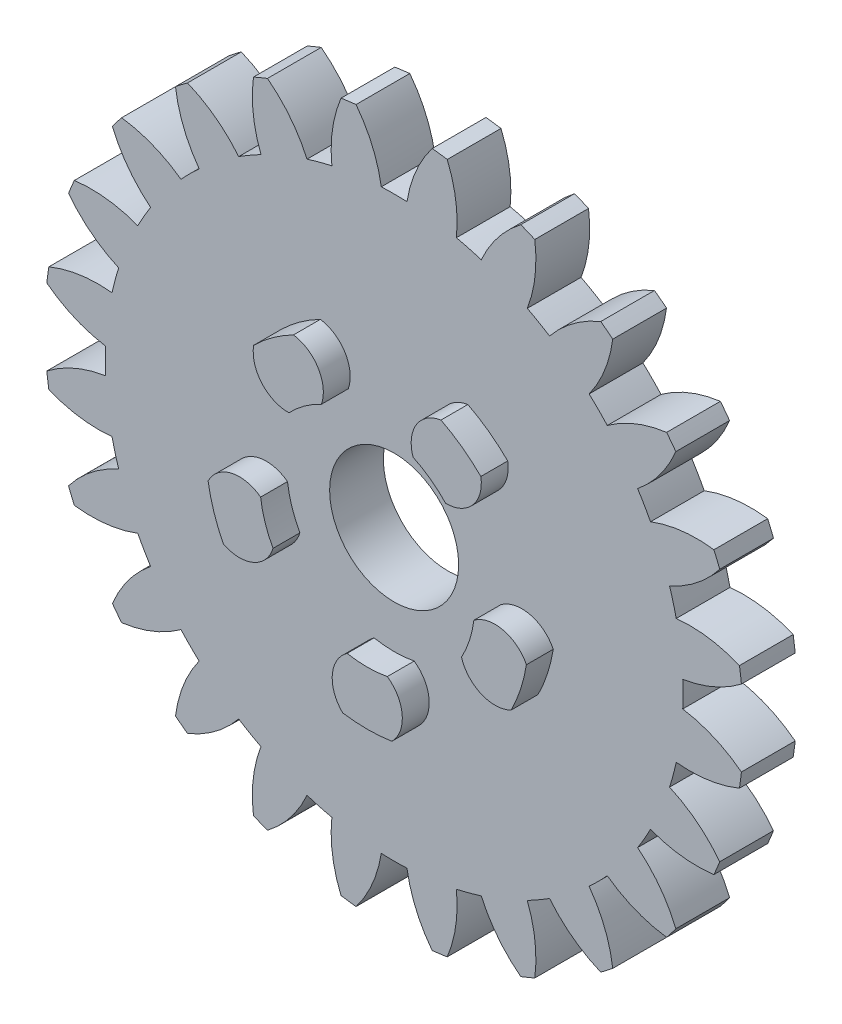
SolidWorks part; units mm, degrees
ref_plane "Front Plane" through (0, 0, 0) normal (0, 0, 1) x (1, 0, 0)
ref_plane "Top Plane" through (0, 0, 0) normal (0, 1, 0) x (1, 0, 0)
ref_plane "Right Plane" through (0, 0, 0) normal (1, 0, 0) x (0, 0, -1)
sketch "Sketch1" plane through (0, 0, 0) normal (0, 0, 1) x (1, 0, 0)
  circle A0 centre (0, 0) radius 3
  arc A96 (-32.3065, 3.5416) -> (-26.8474, 1.1963) centre (-24.9877, 13.0513) ccw
  arc A97 (-26.8474, 1.1963) -> (-26.8474, -1.1963) centre (0, 0) ccw
  arc A98 (-26.8474, -1.1963) -> (-32.3065, -3.5416) centre (-24.9877, -13.0513) ccw
  arc A99 (-32.3065, -3.5416) -> (-32.1223, -4.9406) centre (0, 0) ccw
  arc A100 (-32.1223, -4.9406) -> (-26.2422, -5.7931) centre (-27.5142, 6.1393) ccw
  arc A101 (-26.2422, -5.7931) -> (-25.6229, -8.1041) centre (0, 0) ccw
  arc A102 (-25.6229, -8.1041) -> (-30.289, -11.7824) centre (-20.7583, -19.0739) ccw
  arc A103 (-30.289, -11.7824) -> (-29.749, -13.0861) centre (0, 0) ccw
  arc A104 (-29.749, -13.0861) -> (-23.8486, -12.3877) centre (-28.1656, -1.191) ccw
  arc A105 (-23.8486, -12.3877) -> (-22.6523, -14.4597) centre (0, 0) ccw
  arc A106 (-22.6523, -14.4597) -> (-26.2074, -19.2203) centre (-15.1143, -23.7966) ccw
  arc A107 (-26.2074, -19.2203) -> (-25.3484, -20.3398) centre (0, 0) ccw
  arc A108 (-25.3484, -20.3398) -> (-19.8299, -18.138) centre (-26.8976, -8.4403) ccw
  arc A109 (-19.8299, -18.138) -> (-18.138, -19.8299) centre (0, 0) ccw
  arc A110 (-18.138, -19.8299) -> (-20.3398, -25.3484) centre (-8.4403, -26.8976) ccw
  arc A111 (-20.3398, -25.3484) -> (-19.2203, -26.2074) centre (0, 0) ccw
  arc A112 (-19.2203, -26.2074) -> (-14.4597, -22.6523) centre (-23.7966, -15.1143) ccw
  arc A113 (-14.4597, -22.6523) -> (-12.3877, -23.8486) centre (0, 0) ccw
  arc A114 (-12.3877, -23.8486) -> (-13.0861, -29.749) centre (-1.191, -28.1656) ccw
  arc A115 (-13.0861, -29.749) -> (-11.7824, -30.289) centre (0, 0) ccw
  arc A116 (-11.7824, -30.289) -> (-8.1041, -25.6229) centre (-19.0739, -20.7583) ccw
  arc A117 (-8.1041, -25.6229) -> (-5.7931, -26.2422) centre (0, 0) ccw
  arc A118 (-5.7931, -26.2422) -> (-4.9406, -32.1223) centre (6.1393, -27.5142) ccw
  arc A119 (-4.9406, -32.1223) -> (-3.5416, -32.3065) centre (0, 0) ccw
  arc A120 (-3.5416, -32.3065) -> (-1.1963, -26.8474) centre (-13.0513, -24.9877) ccw
  arc A121 (-1.1963, -26.8474) -> (1.1963, -26.8474) centre (0, 0) ccw
  arc A122 (1.1963, -26.8474) -> (3.5416, -32.3065) centre (13.0513, -24.9877) ccw
  arc A123 (3.5416, -32.3065) -> (4.9406, -32.1223) centre (0, 0) ccw
  arc A124 (4.9406, -32.1223) -> (5.7931, -26.2422) centre (-6.1393, -27.5142) ccw
  arc A125 (5.7931, -26.2422) -> (8.1041, -25.6229) centre (0, 0) ccw
  arc A126 (8.1041, -25.6229) -> (11.7824, -30.289) centre (19.0739, -20.7583) ccw
  arc A127 (11.7824, -30.289) -> (13.0861, -29.749) centre (0, 0) ccw
  arc A128 (13.0861, -29.749) -> (12.3877, -23.8486) centre (1.191, -28.1656) ccw
  arc A129 (12.3877, -23.8486) -> (14.4597, -22.6523) centre (0, 0) ccw
  arc A130 (14.4597, -22.6523) -> (19.2203, -26.2074) centre (23.7966, -15.1143) ccw
  arc A131 (19.2203, -26.2074) -> (20.3398, -25.3484) centre (0, 0) ccw
  arc A132 (20.3398, -25.3484) -> (18.138, -19.8299) centre (8.4403, -26.8976) ccw
  arc A133 (18.138, -19.8299) -> (19.8299, -18.138) centre (0, 0) ccw
  arc A134 (19.8299, -18.138) -> (25.3484, -20.3398) centre (26.8976, -8.4403) ccw
  arc A135 (25.3484, -20.3398) -> (26.2074, -19.2203) centre (0, 0) ccw
  arc A136 (26.2074, -19.2203) -> (22.6523, -14.4597) centre (15.1143, -23.7966) ccw
  arc A137 (22.6523, -14.4597) -> (23.8486, -12.3877) centre (0, 0) ccw
  arc A138 (23.8486, -12.3877) -> (29.749, -13.0861) centre (28.1656, -1.191) ccw
  arc A139 (29.749, -13.0861) -> (30.289, -11.7824) centre (0, 0) ccw
  arc A140 (30.289, -11.7824) -> (25.6229, -8.1041) centre (20.7583, -19.0739) ccw
  arc A141 (25.6229, -8.1041) -> (26.2422, -5.7931) centre (0, 0) ccw
  arc A142 (26.2422, -5.7931) -> (32.1223, -4.9406) centre (27.5142, 6.1393) ccw
  arc A143 (32.1223, -4.9406) -> (32.3065, -3.5416) centre (0, 0) ccw
  arc A144 (32.3065, -3.5416) -> (26.8474, -1.1963) centre (24.9877, -13.0513) ccw
  arc A145 (26.8474, -1.1963) -> (26.8474, 1.1963) centre (0, 0) ccw
  arc A146 (26.8474, 1.1963) -> (32.3065, 3.5416) centre (24.9877, 13.0513) ccw
  arc A147 (32.3065, 3.5416) -> (32.1223, 4.9406) centre (0, 0) ccw
  arc A148 (32.1223, 4.9406) -> (26.2422, 5.7931) centre (27.5142, -6.1393) ccw
  arc A149 (26.2422, 5.7931) -> (25.6229, 8.1041) centre (0, 0) ccw
  arc A150 (25.6229, 8.1041) -> (30.289, 11.7824) centre (20.7583, 19.0739) ccw
  arc A151 (30.289, 11.7824) -> (29.749, 13.0861) centre (0, 0) ccw
  arc A152 (29.749, 13.0861) -> (23.8486, 12.3877) centre (28.1656, 1.191) ccw
  arc A153 (23.8486, 12.3877) -> (22.6523, 14.4597) centre (0, 0) ccw
  arc A154 (22.6523, 14.4597) -> (26.2074, 19.2203) centre (15.1143, 23.7966) ccw
  arc A155 (26.2074, 19.2203) -> (25.3484, 20.3398) centre (0, 0) ccw
  arc A156 (25.3484, 20.3398) -> (19.8299, 18.138) centre (26.8976, 8.4403) ccw
  arc A157 (19.8299, 18.138) -> (18.138, 19.8299) centre (0, 0) ccw
  arc A158 (18.138, 19.8299) -> (20.3398, 25.3484) centre (8.4403, 26.8976) ccw
  arc A159 (20.3398, 25.3484) -> (19.2203, 26.2074) centre (0, 0) ccw
  arc A160 (19.2203, 26.2074) -> (14.4597, 22.6523) centre (23.7966, 15.1143) ccw
  arc A161 (14.4597, 22.6523) -> (12.3877, 23.8486) centre (0, 0) ccw
  arc A162 (12.3877, 23.8486) -> (13.0861, 29.749) centre (1.191, 28.1656) ccw
  arc A163 (13.0861, 29.749) -> (11.7824, 30.289) centre (0, 0) ccw
  arc A164 (11.7824, 30.289) -> (8.1041, 25.6229) centre (19.0739, 20.7583) ccw
  arc A165 (8.1041, 25.6229) -> (5.7931, 26.2422) centre (0, 0) ccw
  arc A166 (5.7931, 26.2422) -> (4.9406, 32.1223) centre (-6.1393, 27.5142) ccw
  arc A167 (4.9406, 32.1223) -> (3.5416, 32.3065) centre (0, 0) ccw
  arc A168 (3.5416, 32.3065) -> (1.1963, 26.8474) centre (13.0513, 24.9877) ccw
  arc A169 (1.1963, 26.8474) -> (-1.1963, 26.8474) centre (0, 0) ccw
  arc A170 (-1.1963, 26.8474) -> (-3.5416, 32.3065) centre (-13.0513, 24.9877) ccw
  arc A171 (-3.5416, 32.3065) -> (-4.9406, 32.1223) centre (0, 0) ccw
  arc A172 (-4.9406, 32.1223) -> (-5.7931, 26.2422) centre (6.1393, 27.5142) ccw
  arc A173 (-5.7931, 26.2422) -> (-8.1041, 25.6229) centre (0, 0) ccw
  arc A174 (-8.1041, 25.6229) -> (-11.7824, 30.289) centre (-19.0739, 20.7583) ccw
  arc A175 (-11.7824, 30.289) -> (-13.0861, 29.749) centre (0, 0) ccw
  arc A176 (-13.0861, 29.749) -> (-12.3877, 23.8486) centre (-1.191, 28.1656) ccw
  arc A177 (-12.3877, 23.8486) -> (-14.4597, 22.6523) centre (0, 0) ccw
  arc A178 (-14.4597, 22.6523) -> (-19.2203, 26.2074) centre (-23.7966, 15.1143) ccw
  arc A179 (-19.2203, 26.2074) -> (-20.3398, 25.3484) centre (0, 0) ccw
  arc A180 (-20.3398, 25.3484) -> (-18.138, 19.8299) centre (-8.4403, 26.8976) ccw
  arc A181 (-18.138, 19.8299) -> (-19.8299, 18.138) centre (0, 0) ccw
  arc A182 (-19.8299, 18.138) -> (-25.3484, 20.3398) centre (-26.8976, 8.4403) ccw
  arc A183 (-25.3484, 20.3398) -> (-26.2074, 19.2203) centre (0, 0) ccw
  arc A184 (-26.2074, 19.2203) -> (-22.6523, 14.4597) centre (-15.1143, 23.7966) ccw
  arc A185 (-22.6523, 14.4597) -> (-23.8486, 12.3877) centre (0, 0) ccw
  arc A186 (-23.8486, 12.3877) -> (-29.749, 13.0861) centre (-28.1656, 1.191) ccw
  arc A187 (-29.749, 13.0861) -> (-30.289, 11.7824) centre (0, 0) ccw
  arc A188 (-30.289, 11.7824) -> (-25.6229, 8.1041) centre (-20.7583, 19.0739) ccw
  arc A189 (-25.6229, 8.1041) -> (-26.2422, 5.7931) centre (0, 0) ccw
  arc A190 (-26.2422, 5.7931) -> (-32.1223, 4.9406) centre (-27.5142, -6.1393) ccw
  arc A191 (-32.1223, 4.9406) -> (-32.3065, 3.5416) centre (0, 0) ccw
  arc A192 (-32.3065, 3.5416) -> (-26.8474, 1.1963) centre (-24.9877, 13.0513) ccw
  arc A193 (-26.8474, 1.1963) -> (-26.8474, -1.1963) centre (0, 0) ccw
  arc A194 (-26.8474, -1.1963) -> (-32.3065, -3.5416) centre (-24.9877, -13.0513) ccw
  arc A195 (-32.3065, -3.5416) -> (-32.1223, -4.9406) centre (0, 0) ccw
  arc A196 (-32.1223, -4.9406) -> (-26.2422, -5.7931) centre (-27.5142, 6.1393) ccw
  arc A197 (-26.2422, -5.7931) -> (-25.6229, -8.1041) centre (0, 0) ccw
  arc A198 (-25.6229, -8.1041) -> (-30.289, -11.7824) centre (-20.7583, -19.0739) ccw
  arc A199 (-30.289, -11.7824) -> (-29.749, -13.0861) centre (0, 0) ccw
  arc A200 (-29.749, -13.0861) -> (-23.8486, -12.3877) centre (-28.1656, -1.191) ccw
  arc A201 (-23.8486, -12.3877) -> (-22.6523, -14.4597) centre (0, 0) ccw
  arc A202 (-22.6523, -14.4597) -> (-26.2074, -19.2203) centre (-15.1143, -23.7966) ccw
  arc A203 (-26.2074, -19.2203) -> (-25.3484, -20.3398) centre (0, 0) ccw
  arc A204 (-25.3484, -20.3398) -> (-19.8299, -18.138) centre (-26.8976, -8.4403) ccw
  arc A205 (-19.8299, -18.138) -> (-18.138, -19.8299) centre (0, 0) ccw
  arc A206 (-18.138, -19.8299) -> (-20.3398, -25.3484) centre (-8.4403, -26.8976) ccw
  arc A207 (-20.3398, -25.3484) -> (-19.2203, -26.2074) centre (0, 0) ccw
  arc A208 (-19.2203, -26.2074) -> (-14.4597, -22.6523) centre (-23.7966, -15.1143) ccw
  arc A209 (-14.4597, -22.6523) -> (-12.3877, -23.8486) centre (0, 0) ccw
  arc A210 (-12.3877, -23.8486) -> (-13.0861, -29.749) centre (-1.191, -28.1656) ccw
  arc A211 (-13.0861, -29.749) -> (-11.7824, -30.289) centre (0, 0) ccw
  arc A212 (-11.7824, -30.289) -> (-8.1041, -25.6229) centre (-19.0739, -20.7583) ccw
  arc A213 (-8.1041, -25.6229) -> (-5.7931, -26.2422) centre (0, 0) ccw
  arc A214 (-5.7931, -26.2422) -> (-4.9406, -32.1223) centre (6.1393, -27.5142) ccw
  arc A215 (-4.9406, -32.1223) -> (-3.5416, -32.3065) centre (0, 0) ccw
  arc A216 (-3.5416, -32.3065) -> (-1.1963, -26.8474) centre (-13.0513, -24.9877) ccw
  arc A217 (-1.1963, -26.8474) -> (1.1963, -26.8474) centre (0, 0) ccw
  arc A218 (1.1963, -26.8474) -> (3.5416, -32.3065) centre (13.0513, -24.9877) ccw
  arc A219 (3.5416, -32.3065) -> (4.9406, -32.1223) centre (0, 0) ccw
  arc A220 (4.9406, -32.1223) -> (5.7931, -26.2422) centre (-6.1393, -27.5142) ccw
  arc A221 (5.7931, -26.2422) -> (8.1041, -25.6229) centre (0, 0) ccw
  arc A222 (8.1041, -25.6229) -> (11.7824, -30.289) centre (19.0739, -20.7583) ccw
  arc A223 (11.7824, -30.289) -> (13.0861, -29.749) centre (0, 0) ccw
  arc A224 (13.0861, -29.749) -> (12.3877, -23.8486) centre (1.191, -28.1656) ccw
  arc A225 (12.3877, -23.8486) -> (14.4597, -22.6523) centre (0, 0) ccw
  arc A226 (14.4597, -22.6523) -> (19.2203, -26.2074) centre (23.7966, -15.1143) ccw
  arc A227 (19.2203, -26.2074) -> (20.3398, -25.3484) centre (0, 0) ccw
  arc A228 (20.3398, -25.3484) -> (18.138, -19.8299) centre (8.4403, -26.8976) ccw
  arc A229 (18.138, -19.8299) -> (19.8299, -18.138) centre (0, 0) ccw
  arc A230 (19.8299, -18.138) -> (25.3484, -20.3398) centre (26.8976, -8.4403) ccw
  arc A231 (25.3484, -20.3398) -> (26.2074, -19.2203) centre (0, 0) ccw
  arc A232 (26.2074, -19.2203) -> (22.6523, -14.4597) centre (15.1143, -23.7966) ccw
  arc A233 (22.6523, -14.4597) -> (23.8486, -12.3877) centre (0, 0) ccw
  arc A234 (23.8486, -12.3877) -> (29.749, -13.0861) centre (28.1656, -1.191) ccw
  arc A235 (29.749, -13.0861) -> (30.289, -11.7824) centre (0, 0) ccw
  arc A236 (30.289, -11.7824) -> (25.6229, -8.1041) centre (20.7583, -19.0739) ccw
  arc A237 (25.6229, -8.1041) -> (26.2422, -5.7931) centre (0, 0) ccw
  arc A238 (26.2422, -5.7931) -> (32.1223, -4.9406) centre (27.5142, 6.1393) ccw
  arc A239 (32.1223, -4.9406) -> (32.3065, -3.5416) centre (0, 0) ccw
  arc A240 (32.3065, -3.5416) -> (26.8474, -1.1963) centre (24.9877, -13.0513) ccw
  arc A241 (26.8474, -1.1963) -> (26.8474, 1.1963) centre (0, 0) ccw
  arc A242 (26.8474, 1.1963) -> (32.3065, 3.5416) centre (24.9877, 13.0513) ccw
  arc A243 (32.3065, 3.5416) -> (32.1223, 4.9406) centre (0, 0) ccw
  arc A244 (32.1223, 4.9406) -> (26.2422, 5.7931) centre (27.5142, -6.1393) ccw
  arc A245 (26.2422, 5.7931) -> (25.6229, 8.1041) centre (0, 0) ccw
  arc A246 (25.6229, 8.1041) -> (30.289, 11.7824) centre (20.7583, 19.0739) ccw
  arc A247 (30.289, 11.7824) -> (29.749, 13.0861) centre (0, 0) ccw
  arc A248 (29.749, 13.0861) -> (23.8486, 12.3877) centre (28.1656, 1.191) ccw
  arc A249 (23.8486, 12.3877) -> (22.6523, 14.4597) centre (0, 0) ccw
  arc A250 (22.6523, 14.4597) -> (26.2074, 19.2203) centre (15.1143, 23.7966) ccw
  arc A251 (26.2074, 19.2203) -> (25.3484, 20.3398) centre (0, 0) ccw
  arc A252 (25.3484, 20.3398) -> (19.8299, 18.138) centre (26.8976, 8.4403) ccw
  arc A253 (19.8299, 18.138) -> (18.138, 19.8299) centre (0, 0) ccw
  arc A254 (18.138, 19.8299) -> (20.3398, 25.3484) centre (8.4403, 26.8976) ccw
  arc A255 (20.3398, 25.3484) -> (19.2203, 26.2074) centre (0, 0) ccw
  arc A256 (19.2203, 26.2074) -> (14.4597, 22.6523) centre (23.7966, 15.1143) ccw
  arc A257 (14.4597, 22.6523) -> (12.3877, 23.8486) centre (0, 0) ccw
  arc A258 (12.3877, 23.8486) -> (13.0861, 29.749) centre (1.191, 28.1656) ccw
  arc A259 (13.0861, 29.749) -> (11.7824, 30.289) centre (0, 0) ccw
  arc A260 (11.7824, 30.289) -> (8.1041, 25.6229) centre (19.0739, 20.7583) ccw
  arc A261 (8.1041, 25.6229) -> (5.7931, 26.2422) centre (0, 0) ccw
  arc A262 (5.7931, 26.2422) -> (4.9406, 32.1223) centre (-6.1393, 27.5142) ccw
  arc A263 (4.9406, 32.1223) -> (3.5416, 32.3065) centre (0, 0) ccw
  arc A264 (3.5416, 32.3065) -> (1.1963, 26.8474) centre (13.0513, 24.9877) ccw
  arc A265 (1.1963, 26.8474) -> (-1.1963, 26.8474) centre (0, 0) ccw
  arc A266 (-1.1963, 26.8474) -> (-3.5416, 32.3065) centre (-13.0513, 24.9877) ccw
  arc A267 (-3.5416, 32.3065) -> (-4.9406, 32.1223) centre (0, 0) ccw
  arc A268 (-4.9406, 32.1223) -> (-5.7931, 26.2422) centre (6.1393, 27.5142) ccw
  arc A269 (-5.7931, 26.2422) -> (-8.1041, 25.6229) centre (0, 0) ccw
  arc A270 (-8.1041, 25.6229) -> (-11.7824, 30.289) centre (-19.0739, 20.7583) ccw
  arc A271 (-11.7824, 30.289) -> (-13.0861, 29.749) centre (0, 0) ccw
  arc A272 (-13.0861, 29.749) -> (-12.3877, 23.8486) centre (-1.191, 28.1656) ccw
  arc A273 (-12.3877, 23.8486) -> (-14.4597, 22.6523) centre (0, 0) ccw
  arc A274 (-14.4597, 22.6523) -> (-19.2203, 26.2074) centre (-23.7966, 15.1143) ccw
  arc A275 (-19.2203, 26.2074) -> (-20.3398, 25.3484) centre (0, 0) ccw
  arc A276 (-20.3398, 25.3484) -> (-18.138, 19.8299) centre (-8.4403, 26.8976) ccw
  arc A277 (-18.138, 19.8299) -> (-19.8299, 18.138) centre (0, 0) ccw
  arc A278 (-19.8299, 18.138) -> (-25.3484, 20.3398) centre (-26.8976, 8.4403) ccw
  arc A279 (-25.3484, 20.3398) -> (-26.2074, 19.2203) centre (0, 0) ccw
  arc A280 (-26.2074, 19.2203) -> (-22.6523, 14.4597) centre (-15.1143, 23.7966) ccw
  arc A281 (-22.6523, 14.4597) -> (-23.8486, 12.3877) centre (0, 0) ccw
  arc A282 (-23.8486, 12.3877) -> (-29.749, 13.0861) centre (-28.1656, 1.191) ccw
  arc A283 (-29.749, 13.0861) -> (-30.289, 11.7824) centre (0, 0) ccw
  arc A284 (-30.289, 11.7824) -> (-25.6229, 8.1041) centre (-20.7583, 19.0739) ccw
  arc A285 (-25.6229, 8.1041) -> (-26.2422, 5.7931) centre (0, 0) ccw
  arc A286 (-26.2422, 5.7931) -> (-32.1223, 4.9406) centre (-27.5142, -6.1393) ccw
  arc A287 (-32.1223, 4.9406) -> (-32.3065, 3.5416) centre (0, 0) ccw
  dimension "D1" = 0
extrude "Boss-Extrude1" add sketch "Sketch1" along normal blind 5 contours A0 | A192 A193 A194 A195 A196 A197 A198 A199 A200 A201 A202 A203 A204 A205 A206 A207 A208 A209 A210 A211 A212 A213 A214 A215 A216 A217 A218 A219 A220 A221 A222 A223 A224 A225 A226 A227 A228 A229 A230 A231 A232 A233 A234 A235 A236 A237 A238 A239 A240 A241 A242 A243 A244 A245 A246 A247 A248 A249 A250 A251 A252 A253 A254 A255 A256 A257 A258 A259 A260 A261 A262 A263 A264 A265 A266 A267 A268 A269 A270 A271 A272 A273 A274 A275 A276 A277 A278 A279 A280 A281 A282 A283 A284 A285 A286 A287
sketch "Sketch2" plane through (0, 0, 0) normal (0, 0, -1) x (-1, 0, 0)
  circle A0 centre (0, 0) radius 6
extrude "Cut-Extrude1" cut sketch "Sketch2" against normal up to next
sketch "Sketch3" plane through (0, 0, 5) normal (0, 0, 1) x (1, 0, 0)
  arc A0 (2.2906, -14.8241) -> (13.3907, -6.7594) centre (0, 0) ccw
  arc A1 (8.7662, -4.8119) -> (13.3907, -6.7594) centre (11.8882, -3.8627) ccw
  arc A2 (1.8675, -9.8241) -> (8.7662, -4.8119) centre (0, 0) ccw
  arc A3 (2.2906, -14.8241) -> (1.8675, -9.8241) centre (0, -12.5) ccw
  arc A4 (-8.7662, -4.8119) -> (-1.8675, -9.8241) centre (0, 0) ccw
  arc A5 (-13.3907, -6.7594) -> (-8.7662, -4.8119) centre (-11.8882, -3.8627) ccw
  arc A6 (-13.3907, -6.7594) -> (-2.2906, -14.8241) centre (0, 0) ccw
  arc A7 (-1.8675, -9.8241) -> (-2.2906, -14.8241) centre (0, -12.5) ccw
  arc A8 (-7.2853, 6.8501) -> (-9.9203, -1.2597) centre (0, 0) ccw
  arc A9 (-10.5665, 10.6465) -> (-7.2853, 6.8501) centre (-7.3473, 10.1127) ccw
  arc A10 (-10.5665, 10.6465) -> (-14.8064, -2.4024) centre (0, 0) ccw
  arc A11 (-9.9203, -1.2597) -> (-14.8064, -2.4024) centre (-11.8882, -3.8627) ccw
  arc A12 (4.2636, 9.0455) -> (-4.2636, 9.0455) centre (0, 0) ccw
  arc A13 (6.8602, 13.3393) -> (4.2636, 9.0455) centre (7.3473, 10.1127) ccw
  arc A14 (6.8602, 13.3393) -> (-6.8602, 13.3393) centre (0, 0) ccw
  arc A15 (-4.2636, 9.0455) -> (-6.8602, 13.3393) centre (-7.3473, 10.1127) ccw
  arc A16 (9.9203, -1.2597) -> (7.2853, 6.8501) centre (0, 0) ccw
  arc A17 (14.8064, -2.4024) -> (9.9203, -1.2597) centre (11.8882, -3.8627) ccw
  arc A18 (14.8064, -2.4024) -> (10.5665, 10.6465) centre (0, 0) ccw
  arc A19 (7.2853, 6.8501) -> (10.5665, 10.6465) centre (7.3473, 10.1127) ccw
  arc A20 (-13.3907, -6.7594) -> (-14.8064, -2.4024) centre (0, 0) cw
  arc A21 (-9.9203, -1.2597) -> (-8.7662, -4.8119) centre (0, 0) ccw
  arc A22 (-4.2636, 9.0455) -> (-7.2853, 6.8501) centre (0, 0) ccw
  arc A23 (-10.5665, 10.6465) -> (-6.8602, 13.3393) centre (0, 0) cw
  arc A24 (7.2853, 6.8501) -> (4.2636, 9.0455) centre (0, 0) ccw
  arc A25 (6.8602, 13.3393) -> (10.5665, 10.6465) centre (0, 0) cw
  arc A26 (8.7662, -4.8119) -> (9.9203, -1.2597) centre (0, 0) ccw
  arc A27 (14.8064, -2.4024) -> (13.3907, -6.7594) centre (0, 0) cw
  arc A28 (-1.8675, -9.8241) -> (1.8675, -9.8241) centre (0, 0) ccw
  arc A29 (2.2906, -14.8241) -> (-2.2906, -14.8241) centre (0, 0) cw
  point P42 (0, 0)
  dimension "D1" = 5
extrude "Boss-Extrude2" add sketch "Sketch3" along normal blind 2.5 contours A23 A9 A22 A15 | A25 A13 A24 A19 | A21 A11 A20 A5 | A29 A3 A28 A7 | A27 A17 A26 A1
